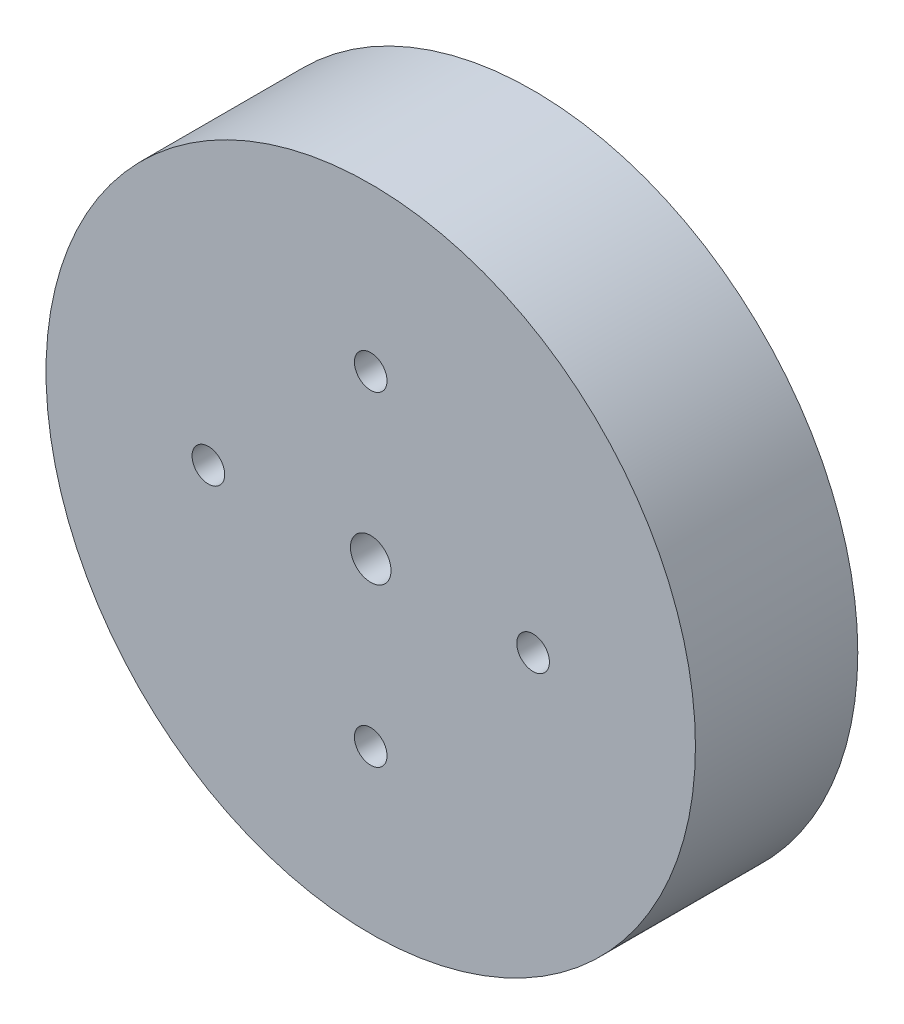
SolidWorks part; units mm, degrees
material "6061-T6 (SS)"
ref_plane "Front Plane" through (0, 0, 0) normal (0, 0, 1) x (1, 0, 0)
ref_plane "Top Plane" through (0, 0, 0) normal (0, 1, 0) x (1, 0, 0)
ref_plane "Right Plane" through (0, 0, 0) normal (1, 0, 0) x (0, 0, -1)
sketch "Sketch1" plane through (0, 0, 0) normal (0, 0, 1) x (1, 0, 0)
  circle A0 centre (0, 0) radius 50.8
  dimension "D1" = 101.6
extrude "Extrude1" add sketch "Sketch1" along normal blind 25.4
hole_wizard "1/4 (0.25) Diameter Hole1" positions "Sketch3" profile "Sketch2" hole size "1/4" standard "Ansi Inch" end condition through all
sketch "Sketch3" plane through (0, 0, 25.4) normal (0, 0, 1) x (1, 0, 0)
  point P1 (0, 0)
sketch "Sketch2" plane through (0, 0, 25.4) normal (1, 0, 0) x (0, -1, 0)
  line L0 (0, 0) -> (0, 25.4)
  line L1 (0, 25.4) -> (3.175, 25.4)
  line L2 (3.175, 25.4) -> (3.175, 0)
  line L5 (3.175, 0) -> (0, 0)
  line L11 (0, -6.35) -> (0, 107.95) construction
  dimension "Thru Hole Dia." = 6.35
  dimension "Thru Hole Depth" = 25.4
sketch "Sketch4" plane through (0, 0, 25.4) normal (0, 0, 1) x (1, 0, 0)
  line L0 (0, 0) -> (25.4, 0) construction
  dimension "D1" = 25.4
hole_wizard "1/4-20 Tapped Hole1" positions "3DSketch1" profile "Sketch5" tap size "1/4-20" standard "Ansi Inch" end condition through all
sketch3d "3DSketch1"
  point P0 (25.4, 0, 25.4)
sketch "Sketch5" plane through (25.4, 0, 25.4) normal (1, 0, 0) x (0, -1, 0)
  line L0 (0, 0) -> (0, 25.4)
  line L1 (0, 25.4) -> (2.5527, 25.4)
  line L2 (2.5527, 25.4) -> (2.5527, 0)
  line L5 (2.5527, 0) -> (0, 0)
  line L11 (0, -6.35) -> (0, 107.95) construction
  dimension "Thread Major Dia." = 5.1054
  dimension "Thru Tap Drill Depth" = 25.4
pattern_circular "CirPattern1" count 4 over 360 about axis through (0, 0, 0) along (0, 0, 1) of "1/4-20 Tapped Hole1"
